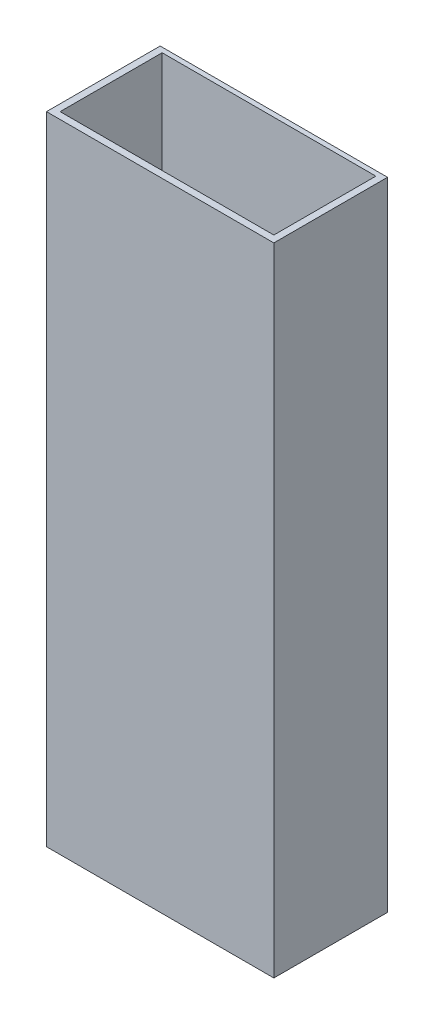
SolidWorks part; units mm, degrees
ref_plane "Front Plane" through (0, 0, 0) normal (0, 0, 1) x (1, 0, 0)
ref_plane "Top Plane" through (0, 0, 0) normal (0, 1, 0) x (1, 0, 0)
ref_plane "Right Plane" through (0, 0, 0) normal (1, 0, 0) x (0, 0, -1)
sketch "Sketch1" plane through (0, 0, 0) normal (0, 1, 0) x (1, 0, 0)
  line L1 (0, 0) -> (50, 0)
  line L2 (0, 0) -> (0, 25)
  line L3 (0, 25) -> (50, 25)
  line L4 (50, 0) -> (50, 25)
  line L9 (48.5, 1.5) -> (1.5, 1.5)
  line L10 (48.5, 1.5) -> (48.5, 23.9344)
  line L11 (48.5, 23.9344) -> (1.5, 23.9344)
  line L12 (1.5, 1.5) -> (1.5, 23.9344)
  line L13 (25, 23.9344) -> (25, 1.5) construction
  line L14 (48.5, 12.7172) -> (1.5, 12.7172) construction
  point P5 (25, 12.7172)
  point P6 (0, 0)
  point P10 (0, 0)
  dimension "D1" = 50
  dimension "D2" = 25
extrude "Boss-Extrude1" add sketch "Sketch1" along normal blind 140
